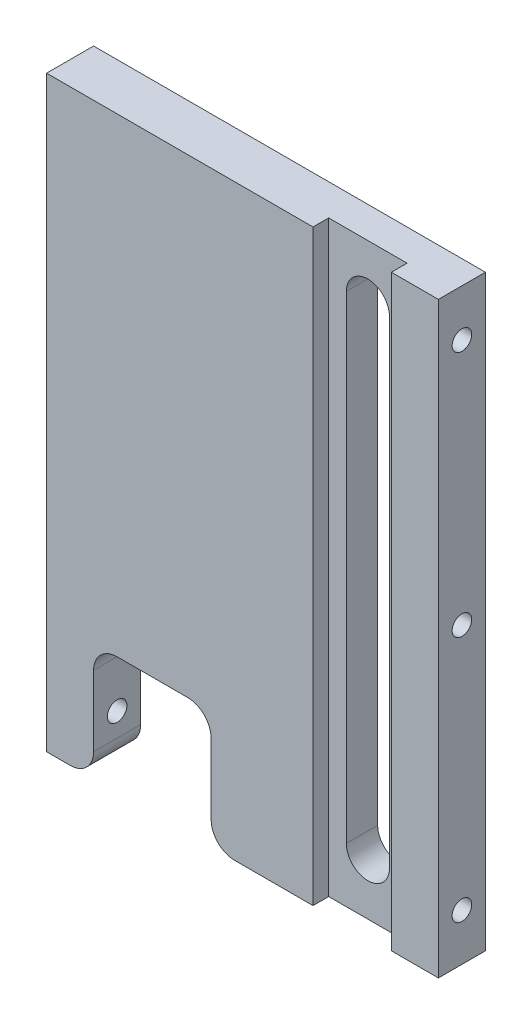
SolidWorks part; units mm, degrees
material "Сплав 2024"
ref_plane "Спереди" through (0, 0, 0) normal (0, 0, 1) x (1, 0, 0)
ref_plane "Сверху" through (0, 0, 0) normal (0, 1, 0) x (1, 0, 0)
ref_plane "Справа" through (0, 0, 0) normal (1, 0, 0) x (0, 0, -1)
sketch "Эскиз1" plane through (0, 0, 0) normal (0, 0, 1) x (1, 0, 0)
  line L1 (-25, 37.5) -> (25, 37.5)
  line L2 (-25, 37.5) -> (-25, -37.5)
  line L3 (-25, -37.5) -> (25, -37.5)
  line L4 (25, 37.5) -> (25, -37.5)
  line L5 (-25, 37.5) -> (25, -37.5) construction
  line L6 (-25, -37.5) -> (25, 37.5) construction
  point P0 (0, 0)
  dimension "D1" = 75
  dimension "D2" = 50
extrude "Бобышка-Вытянуть1" add sketch "Эскиз1" along normal blind 6
sketch "Эскиз2" plane through (0, 0, 6) normal (0, 0, 1) x (1, 0, 0)
  line L0 (14, 37.5) -> (14, -37.5) construction
  line L1 (25, 37.5) -> (-25, 37.5) construction
  line L2 (-25, -37.5) -> (25, -37.5) construction
  line L3 (25, -37.5) -> (25, 37.5) construction
  line L4 (14, 30.5) -> (14, -30.5) construction
  line L5 (16.75, 30.5) -> (16.75, -30.5)
  line L6 (11.25, 30.5) -> (11.25, -30.5)
  arc A0 (16.75, 30.5) -> (11.25, 30.5) centre (14, 30.5) ccw
  arc A1 (11.25, -30.5) -> (16.75, -30.5) centre (14, -30.5) ccw
  point P10 (14, 0)
  dimension "D2" = 2.75
  dimension "D1" = 11
  dimension "D3" = 7
  dimension "D4" = 7
  dimension "D5" = 61
extrude "Вырез-Вытянуть1" cut sketch "Эскиз2" against normal through all
sketch "Эскиз3" plane through (-25, 0, 0) normal (-1, 0, 0) x (0, 0, 1)
  line L0 (3, 37.5) -> (3, -37.5) construction
  line L1 (6, 37.5) -> (0, 37.5) construction
  line L2 (6, -37.5) -> (0, -37.5) construction
  line L3 (0, 0) -> (6, 0) construction
  line L4 (6, 37.5) -> (6, -37.5) construction
  line L5 (0, 31.5) -> (6, 31.5) construction
  line L6 (0, 37.5) -> (0, -37.5) construction
  line L7 (0, -31.5) -> (6, -31.5) construction
  dimension "D1" = 6
  dimension "D2" = 6
hole_wizard "Отверстие обработанное метчиком M3x0.51" positions "Эскиз5" profile "Эскиз4" tap size "M3x0.5" standard "Ansi Metric"
sketch "Эскиз5" plane through (-25, 0, 0) normal (-1, 0, 0) x (0, 0, 1)
  line L0 (0, 31.5) -> (6, 31.5) construction
  line L1 (3, 37.5) -> (3, -37.5) construction
  line L2 (0, -31.5) -> (6, -31.5) construction
  point P0 (3, 31.5)
  point P4 (3, 0)
  point P8 (3, -31.5)
sketch "Эскиз4" plane through (-25, 31.5, 3) normal (0, 1, 0) x (0, 0, 1)
  line L0 (0, 0) -> (0, 6.7511)
  line L1 (0, 6.7511) -> (1.25, 6)
  line L2 (1.25, 6) -> (1.25, 0)
  line L5 (1.25, 0) -> (0, 0)
  line L10 (0, 6.7511) -> (-1.25, 6) construction
  line L11 (0, -6.35) -> (0, 107.95) construction
  dimension "Диаметр сверла" = 2.5
  dimension "Глубина сверла" = 6
  dimension "Угол заточки сверла" = 118
cosmetic thread "Отверстие резьбы1" parameters "D1"=6, "D2"=3
cosmetic thread "Отверстие резьбы2" parameters "D1"=6, "D2"=3
cosmetic thread "Отверстие резьбы3" parameters "D1"=6, "D2"=3
ref_plane "Плоскость1" through (0, 0, 0) normal (-1, 0, 0) x (0, 0, 1)
mirror "Зеркальное отражение1" about plane through (0, 0, 0) normal (-1, 0, 0) of "Отверстие обработанное метчиком M3x0.51"
sketch "Эскиз6" plane through (0, 0, 6) normal (0, 0, 1) x (1, 0, 0)
  line L0 (-25, -37.5) -> (25, -37.5) construction
  line L1 (19, 37.5) -> (9, 37.5)
  line L2 (19, 37.5) -> (19, -37.5)
  line L3 (19, -37.5) -> (9, -37.5)
  line L4 (9, 37.5) -> (9, -37.5)
  line L5 (19, 37.5) -> (9, -37.5) construction
  line L6 (19, -37.5) -> (9, 37.5) construction
  point P0 (14, 0)
  dimension "D1" = 10
extrude "Вырез-Вытянуть2" cut sketch "Эскиз6" against normal blind 2
sketch "Эскиз7" plane through (0, 0, 6) normal (0, 0, 1) x (1, 0, 0)
  line L0 (-11.5, 37.5) -> (-11.5, -37.5) construction
  line L1 (9, 37.5) -> (-25, 37.5) construction
  line L2 (-25, -37.5) -> (9, -37.5) construction
  line L3 (-25, 37.5) -> (-25, -37.5) construction
  line L5 (-19, -22.5) -> (-4, -22.5)
  line L6 (-19, -22.5) -> (-19, -37.5)
  line L7 (-19, -37.5) -> (-4, -37.5)
  line L8 (-4, -22.5) -> (-4, -37.5)
  line L9 (-19, -22.5) -> (-4, -37.5) construction
  line L10 (-19, -37.5) -> (-4, -22.5) construction
  point P8 (-11.5, -30)
  dimension "D1" = 13.5
  dimension "D2" = 15
  dimension "D3" = 15
extrude "Вырез-Вытянуть3" cut sketch "Эскиз7" against normal through all
fillet "Скругление1" radius 3 4 edges at (-19, -37.5, 3) (-4, -37.5, 3) (-4, -22.5, 3) (-19, -22.5, 3)
